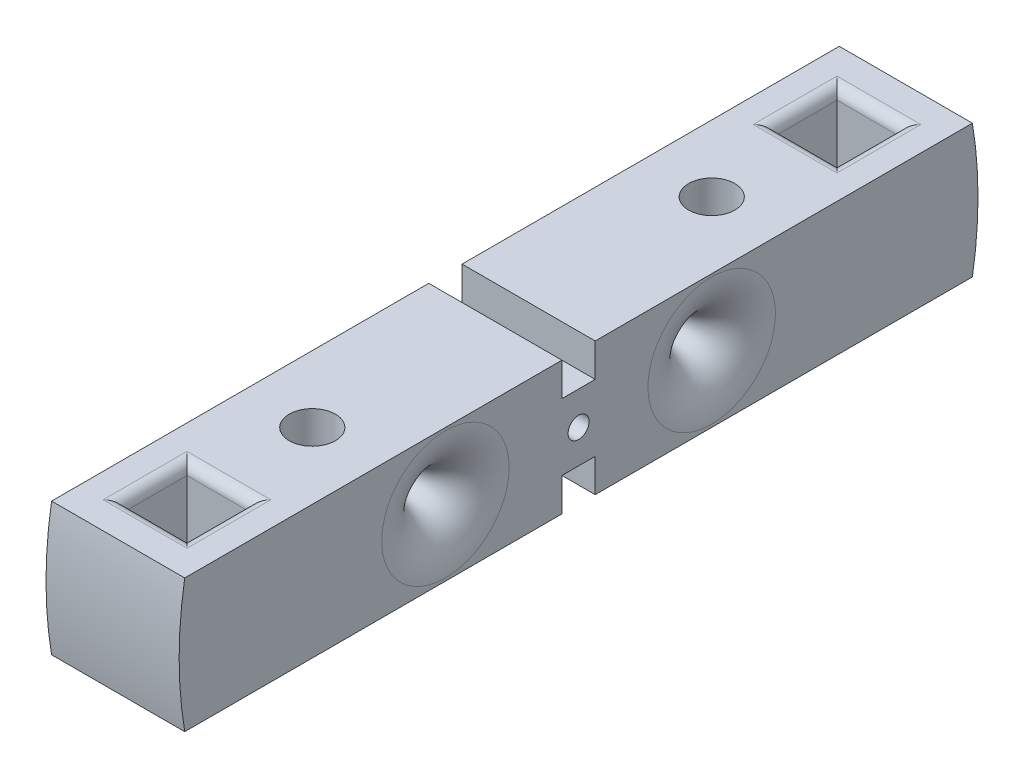
SolidWorks part; units mm, degrees
material "Polyetheretherketone (PEEK)"
ref_plane "Front Plane" through (0, 0, 0) normal (0, 0, 1) x (1, 0, 0)
ref_plane "Top Plane" through (0, 0, 0) normal (0, 1, 0) x (1, 0, 0)
ref_plane "Right Plane" through (0, 0, 0) normal (1, 0, 0) x (0, 0, -1)
sketch "Sketch1" plane through (0, 0, 0) normal (1, 0, 0) x (0, 0, -1)
  line L0 (-18.7836, 3.175) -> (18.7836, 3.175)
  line L1 (0, 0) -> (19.05, 0) construction
  line L2 (-18.7836, -3.175) -> (18.7836, -3.175)
  line L3 (-6.35, 0) -> (0, 0) construction
  arc A0 (-18.7836, 3.175) -> (-18.7836, -3.175) centre (0, 0) ccw
  arc A1 (18.7836, -3.175) -> (18.7836, 3.175) centre (0, 0) ccw
  circle A2 centre (6.35, 0) radius 0.5
  circle A3 centre (-6.35, 0) radius 0.5
  circle A4 centre (0, 0) radius 0.5
  dimension "D1" = 38.1
  dimension "D5" = 1
  dimension "D6" = 1
  dimension "D2" = 3.175
  dimension "D3" = 6.35
  dimension "D4" = 6.35
extrude "Boss-Extrude1" add sketch "Sketch1" along normal blind 6.35
sketch "Sketch2" plane through (0, 3.175, 0) normal (0, 1, 0) x (1, 0, 0)
  line L0 (0, 0) -> (6.35, 0) construction
  line L1 (0, 18.7836) -> (0, -18.7836) construction
  line L2 (6.35, 18.7836) -> (6.35, -18.7836) construction
  line L3 (3.175, 0) -> (3.175, -17) construction
  line L4 (4.675, -17) -> (4.675, -14)
  line L5 (4.675, -17) -> (1.675, -17)
  line L6 (1.675, 17) -> (1.675, 14)
  line L7 (4.675, -14) -> (1.675, -14)
  line L8 (1.675, -17) -> (1.675, -14)
  line L9 (4.675, 14) -> (1.675, 14)
  line L10 (4.675, 17) -> (1.675, 17)
  line L11 (4.675, 17) -> (4.675, 14)
  point P9 (3.175, 14)
  point P13 (3.175, -14)
  dimension "D1" = 3
  dimension "D2" = 14
  dimension "D3" = 1.5
extrude "Cut-Extrude1" cut sketch "Sketch2" against normal blind 6.35
fillet "Fillet1" radius 2.54 4 edges at (0, 0, -6.85) (6.35, 0, -6.85) (0, 0, 5.85) (6.35, 0, 5.85)
hole_wizard "M2 Clearance Hole1" positions "Sketch4" profile "Sketch5" hole size "M2" standard "Ansi Metric"
sketch "Sketch4" plane through (0, -3.175, 0) normal (0, -1, 0) x (1, 0, 0)
  line L0 (3.175, 9.525) -> (3.175, 0) construction
  line L1 (3.175, 0) -> (3.175, -9.525) construction
  line L3 (0, 0) -> (3.175, 0) construction
  line L4 (3.175, 0) -> (6.35, 0) construction
  line L5 (6.35, 18.7836) -> (6.35, -18.7836) construction
  point P0 (3.175, 9.525)
  point P1 (3.175, -9.525)
  dimension "D1" = 9.525
sketch "Sketch5" plane through (3.175, -3.175, 9.525) normal (1, 0, 0) x (0, 0, -1)
  line L0 (0, 0) -> (0, 29.0099)
  line L1 (0, 29.0099) -> (1.1, 28.3489)
  line L2 (1.1, 28.3489) -> (1.1, 0)
  line L5 (1.1, 0) -> (0, 0)
  line L10 (0, 29.0099) -> (-1.1, 28.3489) construction
  line L11 (0, -6.35) -> (0, 107.95) construction
  dimension "Hole Dia." = 2.2
  dimension "Hole Depth" = 28.3489
  dimension "Drill Angle" = 118
fillet "Fillet2" radius 0.5 16 edges at (3.175, 3.175, 17) (1.675, 3.175, 15.5) (4.675, 3.175, 15.5) (3.175, 3.175, 14) (3.175, 3.175, -17) (1.675, 3.175, -15.5) (4.675, 3.175, -15.5) (3.175, 3.175, -14) (3.175, -3.175, -17) (1.675, -3.175, -15.5) (4.675, -3.175, -15.5) (3.175, -3.175, -14) (3.175, -3.175, 14) (4.675, -3.175, 15.5) (1.675, -3.175, 15.5) (3.175, -3.175, 17)
sketch "Sketch6" plane through (0, 0, 0) normal (-1, 0, 0) x (0, 0, 1)
  line L0 (0, 3.175) -> (0, -3.175) construction
  line L1 (-18.7836, 3.175) -> (18.7836, 3.175) construction
  line L2 (18.7836, -3.175) -> (-18.7836, -3.175) construction
  line L4 (-0.7937, -3.175) -> (0.7937, -3.175)
  line L5 (-0.7937, -3.175) -> (-0.7937, -1.5875)
  line L6 (-0.7937, -1.5875) -> (0.7937, -1.5875)
  line L7 (0.7937, -3.175) -> (0.7937, -1.5875)
  line L8 (-0.7937, 3.175) -> (0.7937, 3.175)
  line L9 (-0.7937, 3.175) -> (-0.7937, 1.5875)
  line L10 (-0.7937, 1.5875) -> (0.7938, 1.5875)
  line L11 (0.7937, 3.175) -> (0.7938, 1.5875)
  dimension "D1" = 1.5875
extrude "Cut-Extrude2" cut sketch "Sketch6" against normal through all
